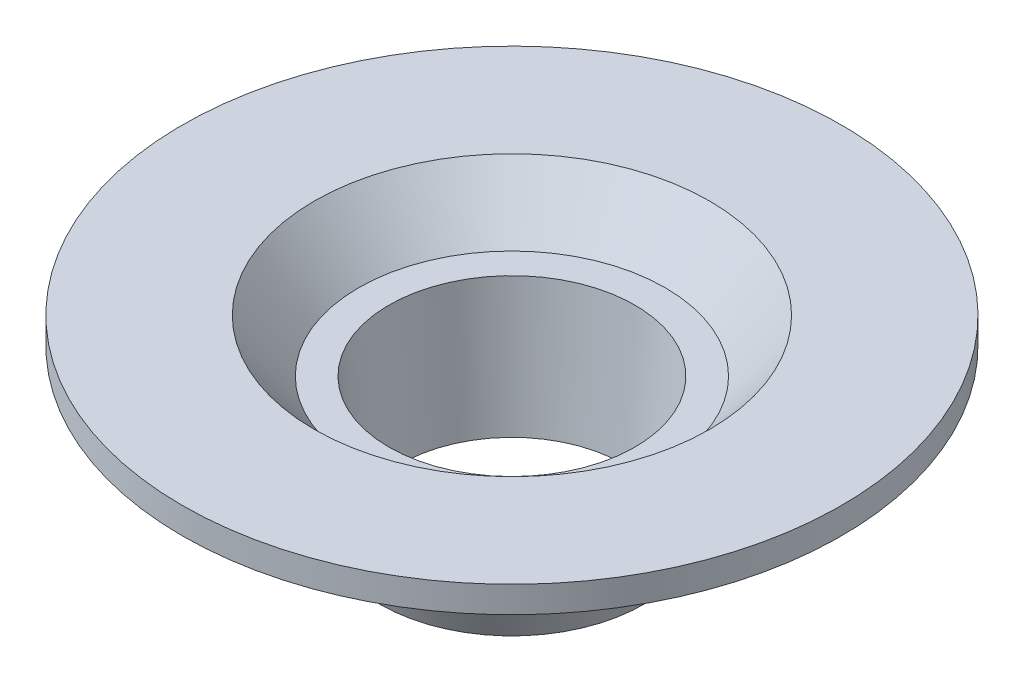
SolidWorks part; units mm, degrees
ref_plane "Front Plane" through (0, 0, 0) normal (0, 0, 1) x (1, 0, 0)
ref_plane "Top Plane" through (0, 0, 0) normal (0, 1, 0) x (1, 0, 0)
ref_plane "Right Plane" through (0, 0, 0) normal (1, 0, 0) x (0, 0, -1)
sketch "Sketch2" plane through (0, 0, 0) normal (0, 0, 1) x (1, 0, 0)
  line L0 (0, 14.4491) -> (0, -14.3844) construction
  line L1 (4.2261, 0) -> (5, 0)
  line L2 (5, 0) -> (6.5583, 4)
  line L3 (6.5583, 4) -> (8.5, 4)
  line L4 (8.5, 4) -> (10.4307, 6)
  line L5 (10.4307, 6) -> (12.5, 6)
  line L6 (12.5, 6) -> (12.5, 7)
  line L7 (12.5, 7) -> (7.5, 7)
  line L8 (7.5, 7) -> (5.8102, 5)
  line L9 (5.8102, 5) -> (4.6661, 5)
  line L10 (4.6661, 5) -> (4.2261, 0)
  point P5 (4.6661, 5)
  point P14 (6.6903, 4)
  point P15 (10.4307, 6)
  point P16 (5.8102, 5)
  dimension "D1" = 4
  dimension "D2" = 5
  dimension "D3" = 2
  dimension "D4" = 1
  dimension "D5" = 12.5
  dimension "D6" = 8.5
  dimension "D7" = 7.5
  dimension "D9" = 5
  dimension "D10" = 4
revolve "Revolve1" add sketch "Sketch2" angle 360 about L0
